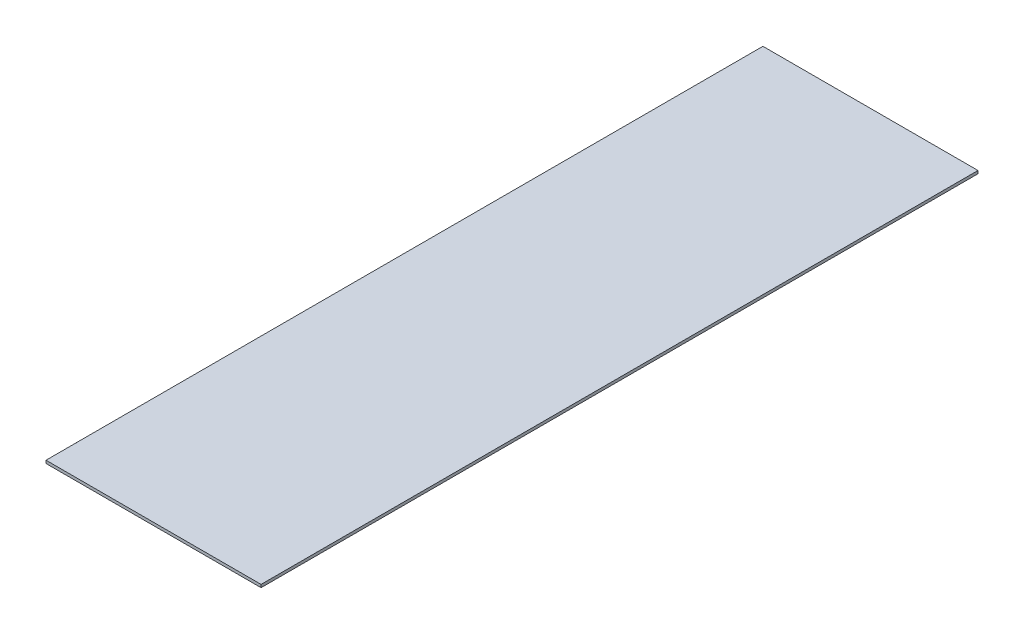
SolidWorks part; units mm, degrees
ref_plane "前视基准面" through (0, 0, 0) normal (0, 0, 1) x (1, 0, 0)
ref_plane "上视基准面" through (0, 0, 0) normal (0, 1, 0) x (1, 0, 0)
ref_plane "右视基准面" through (0, 0, 0) normal (1, 0, 0) x (0, 0, -1)
sketch "草图1" plane through (0, 0, 0) normal (0, 1, 0) x (1, 0, 0)
  line L1 (-150, -500) -> (150, -500)
  line L2 (-150, -500) -> (-150, 500)
  line L3 (-150, 500) -> (150, 500)
  line L4 (150, -500) -> (150, 500)
  line L5 (-150, -500) -> (150, 500) construction
  line L6 (-150, 500) -> (150, -500) construction
  point P0 (0, 0)
  dimension "D1" = 300
  dimension "D2" = 1000
extrude "凸台-拉伸1" add sketch "草图1" along normal blind 4
